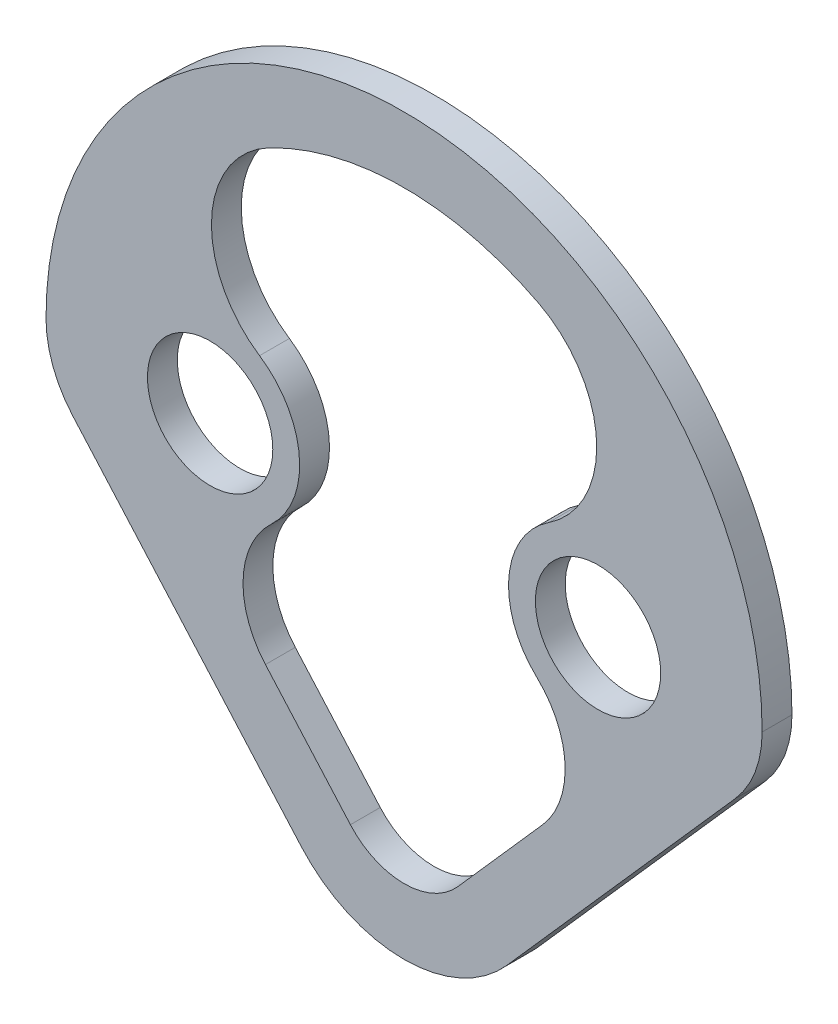
SolidWorks part; units mm, degrees
ref_plane "Płaszczyzna przednia" through (0, 0, 0) normal (0, 0, 1) x (1, 0, 0)
ref_plane "Płaszczyzna górna" through (0, 0, 0) normal (0, 1, 0) x (1, 0, 0)
ref_plane "Płaszczyzna prawa" through (0, 0, 0) normal (1, 0, 0) x (0, 0, -1)
sketch "Szkic1" plane through (0, 0, 0) normal (0, 0, 1) x (1, 0, 0)
  line L0 (0, -51.6088) -> (0, 100) construction
  line L1 (-114.9059, 40) -> (123.5799, 40) construction
  line L4 (-17.2388, -15.2257) -> (-55.4912, 28.0842)
  line L5 (17.2388, -15.2257) -> (55.4912, 28.0842)
  line L6 (-23.2323, 8.1767) -> (-8.9942, -7.9439)
  line L7 (8.9942, -7.9439) -> (23.2323, 8.1767)
  circle A0 centre (-32.5, 40) radius 10.5
  circle A1 centre (32.5, 40) radius 10.5
  arc A4 (-17.2388, -15.2257) -> (17.2388, -15.2257) centre (0, 0) ccw
  arc A5 (-60, 40) -> (60, 40) centre (0, 40) cw
  arc A6 (-60, 40) -> (-55.4912, 28.0842) centre (-42, 40) ccw
  arc A7 (60, 40) -> (55.4912, 28.0842) centre (42, 40) cw
  arc A8 (-8.9942, -7.9439) -> (8.9942, -7.9439) centre (0, 0) ccw
  arc A10 (22.2448, 29.0533) -> (24.2185, 52.5067) centre (32.5, 40) cw
  arc A11 (24.2185, 52.5067) -> (22.5728, 83.491) centre (14.2808, 67.5147) ccw
  arc A12 (22.5728, 83.491) -> (-22.5728, 83.491) centre (0, 40) ccw
  arc A13 (-22.5728, 83.491) -> (-24.2185, 52.5067) centre (-14.2808, 67.5147) ccw
  arc A14 (-24.2185, 52.5067) -> (-22.2448, 29.0533) centre (-32.5, 40) cw
  arc A15 (-22.2448, 29.0533) -> (-23.2323, 8.1767) centre (-11.9896, 18.1066) ccw
  arc A16 (22.2448, 29.0533) -> (23.2323, 8.1767) centre (11.9896, 18.1066) cw
  point P16 (0, 40)
  point P44 (0, 89)
  dimension "D2" = 21
  dimension "D5" = 23
  dimension "D6" = 60
  dimension "D7" = 18
  dimension "D8" = 11
  dimension "D9" = 15
  dimension "D10" = 15
  dimension "D11" = 18
  dimension "D12" = 18
  dimension "D13" = 11
  dimension "D14" = 15
  dimension "D15" = 15
  dimension "D1" = 40
  dimension "D3" = 65
  dimension "D4" = 32.5
extrude "Dodanie-wyciągnięcie1" add sketch "Szkic1" along normal blind 5
